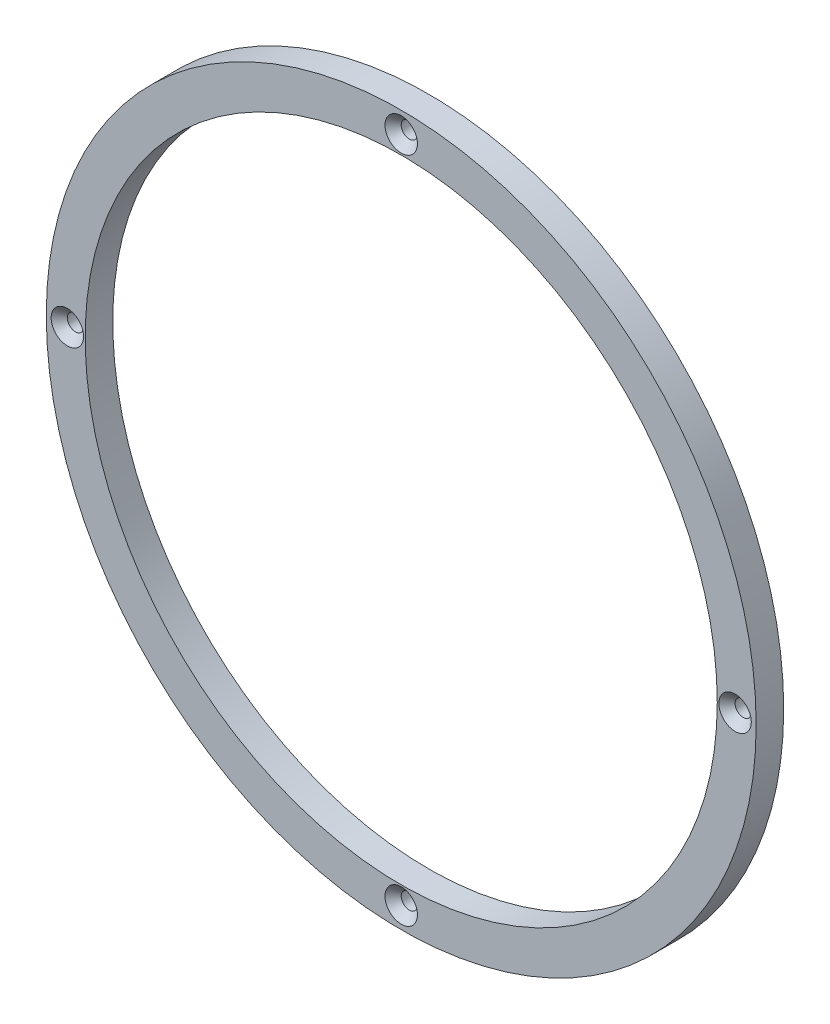
SolidWorks part; units mm, degrees
material "Lega 1060"
ref_plane "Piano frontale" through (0, 0, 0) normal (0, 0, 1) x (1, 0, 0)
ref_plane "Piano superiore" through (0, 0, 0) normal (0, 1, 0) x (1, 0, 0)
ref_plane "Piano destro" through (0, 0, 0) normal (1, 0, 0) x (0, 0, -1)
sketch "Schizzo1" plane through (0, 0, 0) normal (0, 0, 1) x (1, 0, 0)
  circle A0 centre (0, 0) radius 97.5
  circle A1 centre (0, 0) radius 109.5
  dimension "D1" = 195
  dimension "D2" = 12
extrude "Estrusione-Estrusione1" add sketch "Schizzo1" along normal blind 8.5 contours A1 A0 | A0
hole_wizard "Foro svasato per Vite M4 a testa svasata cilindrica1" positions "Schizzo5" profile "Schizzo3" countersink size "M4" standard "DIN" end condition through all
sketch "Schizzo5" plane through (0, 0, 8.5) normal (0, 0, 1) x (1, 0, 0)
  line L0 (0, -4.675) -> (0, 4.675) construction
  circle A1 centre (0, 0) radius 97.5 construction
  point P0 (0, 103)
  dimension "D1" = 5.5
sketch "Schizzo3" plane through (0, 103, 8.5) normal (1, 0, 0) x (0, -1, 0)
  line L0 (0, 0) -> (0, 8.5)
  line L1 (0, 8.5) -> (2.5, 8.5)
  line L2 (2.5, 8.5) -> (2.5, 2.5)
  line L3 (2.5, 2.5) -> (5, 0)
  line L5 (5, 0) -> (0, 0)
  line L6 (-2.5, 2.5) -> (-5, 0) construction
  line L11 (0, -6.35) -> (0, 107.95) construction
  dimension "Thru Hole Dia." = 5
  dimension "Thru Hole Depth" = 8.5
  dimension "Near C'Sink Dia." = 10
  dimension "Near C'Sink Angle" = 90
pattern_circular "RipetizioneCircolare1" count 4 over 360 about axis through (0, 0, 0) along (0, 0, 1) of "Foro svasato per Vite M4 a testa svasata cilindrica1"
